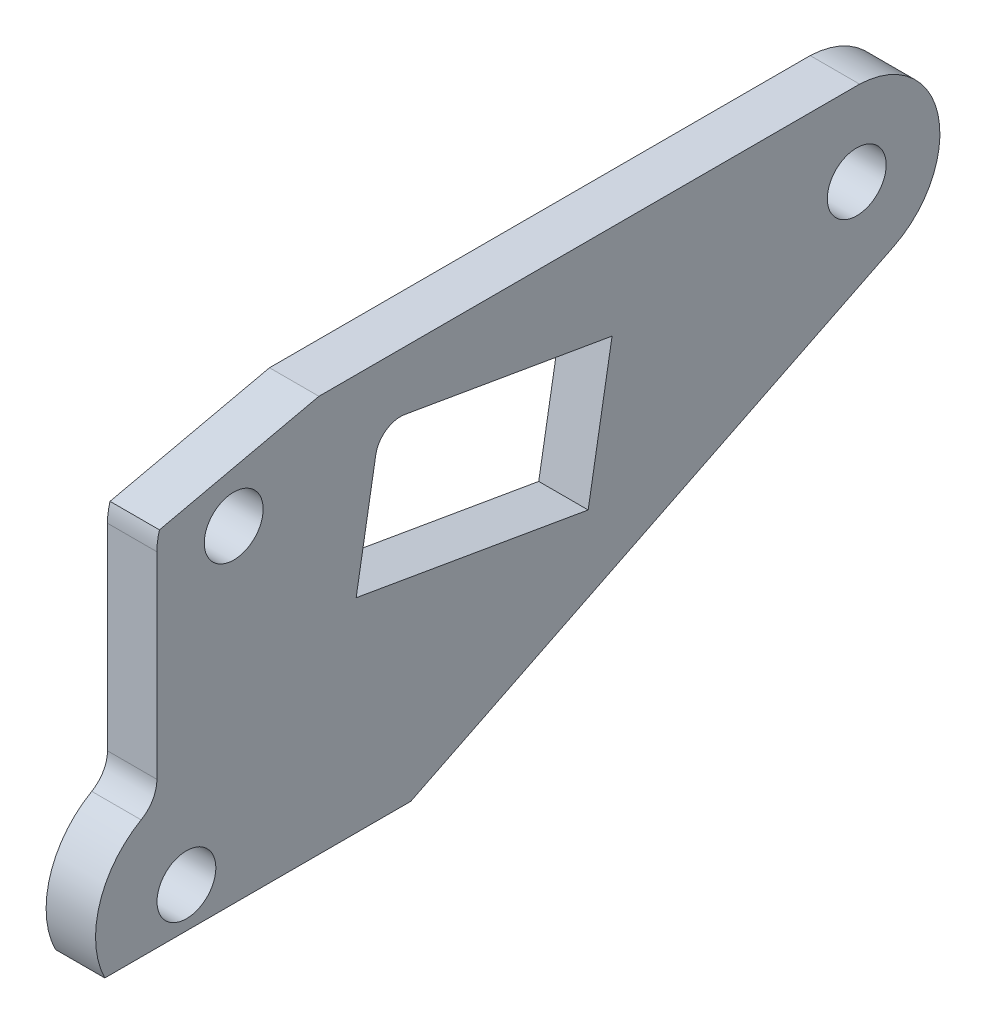
SolidWorks part; units mm, degrees
material "Hardboard"
ref_plane "Front Plane" through (0, 0, 0) normal (0, 0, 1) x (1, 0, 0)
ref_plane "Top Plane" through (0, 0, 0) normal (0, 1, 0) x (1, 0, 0)
ref_plane "Right Plane" through (0, 0, 0) normal (1, 0, 0) x (0, 0, -1)
sketch "Sketch1" plane through (0, 0, 0) normal (1, 0, 0) x (0, 0, -1)
  line L0 (-36.0875, -25.3719) -> (-39.4678, -27.045)
  line L1 (-56.6254, 2.387) -> (-56.6254, -13.5592)
  line L2 (-56.6254, -43.9437) -> (-43.7075, -43.9437)
  line L3 (-43.7075, -43.9437) -> (-43.7075, -33.8742)
  line L4 (-43.7075, -20.39) -> (-26.0228, -20.39) construction
  line L5 (6.73, -20.39) -> (6.73, 6.726) construction
  line L6 (0.2329, 6.726) -> (0, 0) construction
  line L7 (6.73, 0) -> (0, 0) construction
  line L8 (-36.5684, 1.976) -> (-19.7977, -0.9146)
  line L9 (-38.916, 0.3187) -> (-40.5041, -8.8947)
  line L10 (-19.7977, -0.9146) -> (-21.7309, -12.1305)
  line L11 (-40.5041, -8.8947) -> (-21.7309, -12.1305)
  line L12 (-45.5531, -38.8637) -> (-47.5851, -38.8637) construction
  line L13 (-43.5151, 11.806) -> (-16.804, 11.806)
  line L14 (-16.804, 11.806) -> (-16.804, 18.009)
  line L15 (-16.804, 18.009) -> (-52.4758, 18.009)
  line L16 (-52.4758, 18.009) -> (-52.4758, 5.3138) construction
  line L17 (-43.5151, 6.726) -> (0.2329, 6.726)
  line L18 (-42.8121, -7.8827) -> (-43.2653, 4.8092) construction
  line L19 (0.2329, 6.726) -> (6.73, 6.726) construction
  line L20 (-26.0228, -20.39) -> (6.73, -20.39) construction
  line L21 (-26.0228, -20.39) -> (2.9855, -6.0316)
  line L22 (-26.0228, -20.39) -> (-36.0875, -25.3719)
  line L23 (-43.7075, -29.3153) -> (-43.7075, -20.39) construction
  line L24 (-56.6254, -15.1828) -> (-56.6254, -29.0916) construction
  line L25 (-56.6254, -30.7152) -> (-56.6254, -43.9437)
  line L26 (-36.0875, -25.3719) -> (-60.8399, -25.3719)
  line L28 (-56.4195, 3.8188) -> (-43.5151, 6.726)
  circle A0 centre (0, 0) radius 2.3813
  circle A1 centre (-45.5531, -38.8637) radius 0.75
  circle A2 centre (-47.5851, -38.8637) radius 0.75
  circle A3 centre (-49.6171, -38.8637) radius 0.75
  circle A4 centre (-51.6491, -38.8637) radius 0.75
  circle A5 centre (-54.2362, -22.1372) radius 2.3812
  circle A6 centre (-50.4101, 1.0794) radius 2.3812
  circle A7 centre (-53.6811, -38.8637) radius 0.75
  arc A8 (-43.5151, 6.726) -> (-43.5151, 11.806) centre (-43.5151, 9.266) cw
  arc A9 (-52.4758, 18.009) -> (-54.597, 6.4483) centre (-59.8045, 13.3788) cw
  arc A10 (0.2329, 6.726) -> (2.9855, -6.0316) centre (0, 0) cw
  arc A11 (-43.7075, -33.8742) -> (-39.4678, -27.045) centre (-36.0875, -33.8742) cw
  arc A12 (-56.6254, 2.387) -> (-54.597, 6.4483) centre (-51.5454, 2.387) cw
  arc A13 (-57.8999, -15.7615) -> (-60.8399, -25.3719) centre (-54.2362, -22.1372) ccw
  arc A14 (-56.6254, -13.5592) -> (-57.8999, -15.7615) centre (-59.1654, -13.5592) cw
  arc A15 (-56.6254, -30.7152) -> (-57.8999, -28.5129) centre (-59.1654, -30.7152) ccw
  arc A16 (-38.916, 0.3187) -> (-36.5684, 1.976) centre (-36.9135, -0.0265) cw
  arc A17 (-60.8399, -25.3719) -> (-57.8999, -28.5129) centre (-54.2362, -22.1372) ccw
  point P61 (-38.5709, 2.3212)
  dimension "D1" = 4.7625
  dimension "D2" = 1.5
  dimension "D9" = 7.62
  dimension "D10" = 5.08
  dimension "D11" = 2.54
  dimension "D12" = 2.54
  dimension "D13" = 2.032
  dimension "D3" = 5.08
  dimension "D5" = 2.032
  dimension "D6" = 19.05
  dimension "D7" = 6.203
  dimension "D8" = 5.08
  dimension "D4" = 5
extrude "Boss-Extrude1" add sketch "Sketch1" along normal mid plane 4 contours L1 A14 A13 L26 L22 L21 A10 L17 L28 A12 A0 A5 A6 L9 A16 L8 L10 L11
